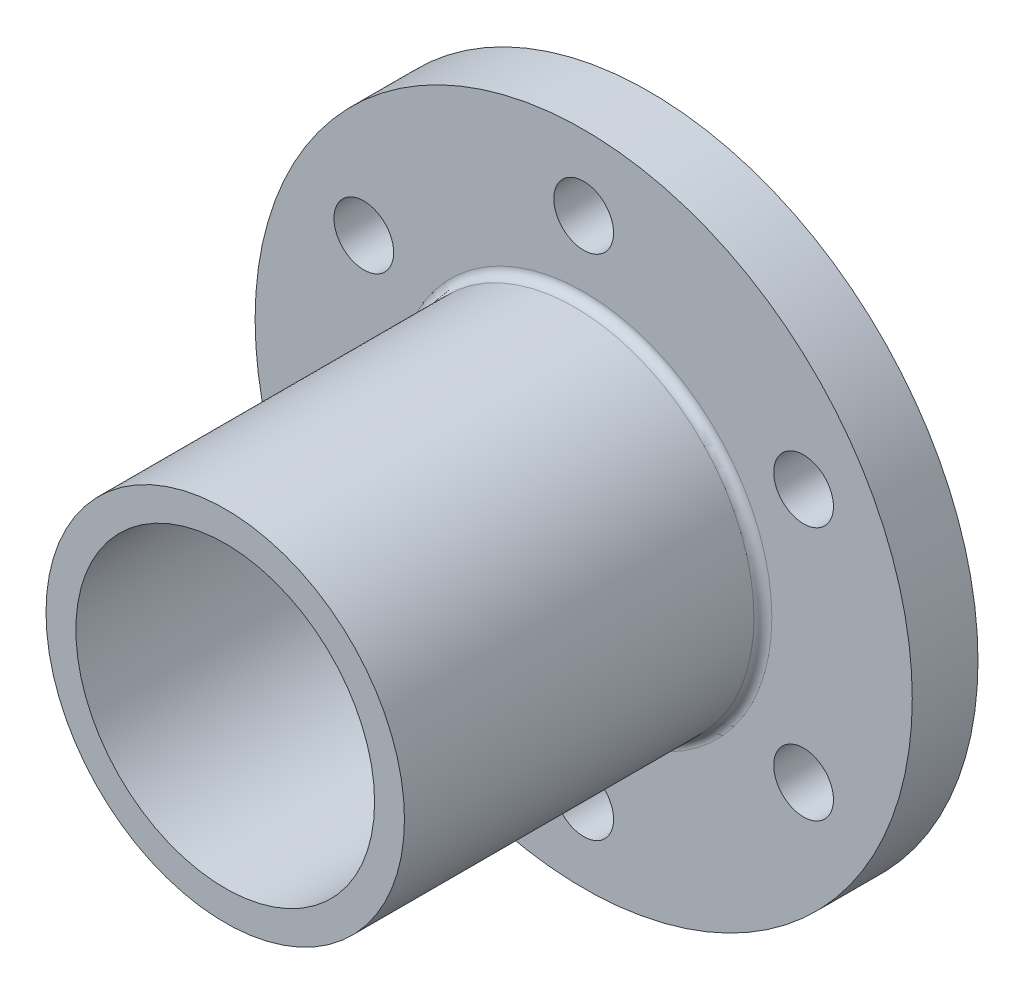
SolidWorks part; units mm, degrees
material "Malleable Cast Iron"
ref_plane "Front Plane" through (0, 0, 0) normal (0, 0, 1) x (1, 0, 0)
ref_plane "Top Plane" through (0, 0, 0) normal (0, 1, 0) x (1, 0, 0)
ref_plane "Right Plane" through (0, 0, 0) normal (1, 0, 0) x (0, 0, -1)
sketch "Sketch2" plane through (0, 0, 0) normal (0, 0, 1) x (1, 0, 0)
  circle A0 centre (0, 0) radius 110
  dimension "D1" = 220
extrude "Boss-Extrude1" add sketch "Sketch2" along normal blind 22
sketch "Sketch3" plane through (0, 0, 22) normal (0, 0, 1) x (1, 0, 0)
  circle A0 centre (0, 0) radius 60
  dimension "D1" = 120
extrude "Boss-Extrude2" add sketch "Sketch3" along normal blind 120
sketch "Sketch4" plane through (0, 0, 142) normal (0, 0, 1) x (1, 0, 0)
  circle A0 centre (0, 0) radius 50
  dimension "D1" = 100
extrude "Cut-Extrude1" cut sketch "Sketch4" against normal blind 207
sketch "Sketch5" plane through (0, 0, 22) normal (0, 0, 1) x (1, 0, 0)
  circle A0 centre (0, 85) radius 10
  circle A1 centre (73.6122, 42.5) radius 10
  circle A2 centre (73.6122, -42.5) radius 10
  circle A3 centre (0, -85) radius 10
  circle A4 centre (-73.6122, -42.5) radius 10
  circle A5 centre (-73.6122, 42.5) radius 10
  point P16 (0, 0)
  dimension "D1" = 20
  dimension "D2" = 85
  dimension "D3" = 6
extrude "Cut-Extrude2" cut sketch "Sketch5" against normal through all
fillet "Fillet1" radius 3 1 edges at (60, 0, 22)
